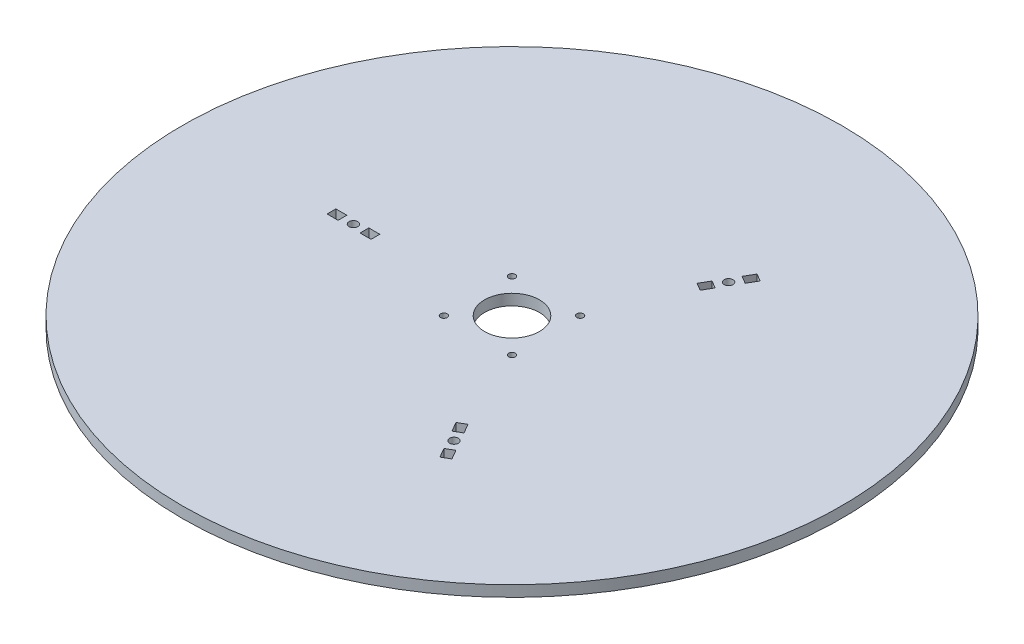
SolidWorks part; units mm, degrees
ref_plane "前视基准面" through (0, 0, 0) normal (0, 0, 1) x (1, 0, 0)
ref_plane "上视基准面" through (0, 0, 0) normal (0, 1, 0) x (1, 0, 0)
ref_plane "右视基准面" through (0, 0, 0) normal (1, 0, 0) x (0, 0, -1)
sketch "草图1" plane through (0, 0, 0) normal (0, 1, 0) x (1, 0, 0)
  line L0 (-72.1688, 0) -> (36.0844, -62.5) construction
  line L1 (15.5, -15.5) -> (-15.5, -15.5) construction
  line L2 (15.5, -15.5) -> (15.5, 15.5) construction
  line L3 (15.5, 15.5) -> (-15.5, 15.5) construction
  line L4 (-15.5, -15.5) -> (-15.5, 15.5) construction
  line L5 (15.5, -15.5) -> (-15.5, 15.5) construction
  line L6 (15.5, 15.5) -> (-15.5, -15.5) construction
  line L7 (-82.1688, 10) -> (-62.1688, 10) construction
  line L8 (-82.1688, -10) -> (-102.1688, -10) construction
  line L9 (-82.1688, -10) -> (-82.1688, 10) construction
  line L10 (-82.1688, 10) -> (-102.1688, 10) construction
  line L11 (-102.1688, -10) -> (-102.1688, 10) construction
  line L12 (-82.1688, -10) -> (-102.1688, 10) construction
  line L13 (-82.1688, 10) -> (-102.1688, -10) construction
  line L14 (-62.1688, 10) -> (-62.1688, -10) construction
  line L15 (-62.1688, -10) -> (-82.1688, -10) construction
  line L16 (-82.1688, 10) -> (-62.1688, -10) construction
  line L17 (36.8523, 67.8301) -> (40.3164, 65.8301)
  line L18 (-62.1688, -2) -> (-67.1688, -2)
  line L19 (-62.1688, -2) -> (-62.1688, 2)
  line L20 (-62.1688, 2) -> (-67.1688, 2)
  line L21 (-67.1688, -2) -> (-67.1688, 2)
  line L22 (-62.1688, -2) -> (-67.1688, 2) construction
  line L23 (-62.1688, 2) -> (-67.1688, -2) construction
  line L24 (-77.1688, -2) -> (-82.1688, -2)
  line L25 (-77.1688, -2) -> (-77.1688, 2)
  line L26 (-77.1688, 2) -> (-82.1688, 2)
  line L27 (-82.1688, -2) -> (-82.1688, 2)
  line L28 (-77.1688, -2) -> (-82.1688, 2) construction
  line L29 (-77.1688, 2) -> (-82.1688, -2) construction
  line L30 (36.8523, 67.8301) -> (39.3523, 72.1603)
  line L31 (39.3523, 72.1603) -> (42.8164, 70.1603)
  line L32 (40.3164, 65.8301) -> (42.8164, 70.1603)
  line L33 (29.3523, 54.8397) -> (32.8164, 52.8397)
  line L34 (29.3523, 54.8397) -> (31.8523, 59.1699)
  line L35 (31.8523, 59.1699) -> (35.3164, 57.1699)
  line L36 (32.8164, 52.8397) -> (35.3164, 57.1699)
  line L37 (40.3164, -65.8301) -> (36.8523, -67.8301)
  line L38 (40.3164, -65.8301) -> (42.8164, -70.1603)
  line L39 (42.8164, -70.1603) -> (39.3523, -72.1603)
  line L40 (36.8523, -67.8301) -> (39.3523, -72.1603)
  line L41 (32.8164, -52.8397) -> (29.3523, -54.8397)
  line L42 (32.8164, -52.8397) -> (35.3164, -57.1699)
  line L43 (35.3164, -57.1699) -> (31.8523, -59.1699)
  line L44 (29.3523, -54.8397) -> (31.8523, -59.1699)
  line L45 (49.7446, 66.1603) -> (59.7446, 83.4808) construction
  line L46 (42.4241, 93.4808) -> (59.7446, 83.4808) construction
  line L47 (32.4241, 76.1603) -> (42.4241, 93.4808) construction
  line L48 (32.4241, 76.1603) -> (49.7446, 66.1603) construction
  line L49 (32.4241, -76.1603) -> (42.4241, -93.4808) construction
  line L50 (59.7446, -83.4808) -> (42.4241, -93.4808) construction
  line L51 (49.7446, -66.1603) -> (59.7446, -83.4808) construction
  line L52 (49.7446, -66.1603) -> (32.4241, -76.1603) construction
  line L53 (29.7446, 31.5192) -> (39.7446, 48.8397) construction
  line L54 (-42.1688, -10) -> (-62.1688, -10) construction
  line L55 (-42.1688, -10) -> (-42.1688, 10) construction
  line L56 (-42.1688, 10) -> (-62.1688, 10) construction
  line L57 (-62.1688, -10) -> (-62.1688, 10) construction
  line L58 (-42.1688, -10) -> (-62.1688, 10) construction
  line L59 (-42.1688, 10) -> (-62.1688, -10) construction
  line L60 (12.4241, 41.5192) -> (29.7446, 31.5192) construction
  line L61 (12.4241, 41.5192) -> (22.4241, 58.8397) construction
  line L62 (39.7446, 48.8397) -> (22.4241, 58.8397) construction
  line L63 (12.4241, -41.5192) -> (22.4241, -58.8397) construction
  line L64 (29.7446, -31.5192) -> (12.4241, -41.5192) construction
  line L65 (29.7446, -31.5192) -> (39.7446, -48.8397) construction
  line L66 (22.4241, -58.8397) -> (39.7446, -48.8397) construction
  circle A0 centre (0, 0) radius 150
  circle A1 centre (-15.5, 15.5) radius 1.5
  circle A2 centre (15.5, 15.5) radius 1.5
  circle A3 centre (15.5, -15.5) radius 1.5
  circle A4 centre (-15.5, -15.5) radius 1.5
  circle A5 centre (0, 0) radius 12.5
  circle A6 centre (-72.1688, 0) radius 2
  circle A7 centre (36.0844, 62.5) radius 2
  circle A8 centre (36.0844, -62.5) radius 2
  circle A14 centre (0, 0) radius 72.1688 construction
  point P17 (0, 0)
  point P18 (-92.1688, 0)
  point P27 (-79.6688, 0)
  point P28 (-72.1688, 0)
  point P29 (-64.6688, 0)
  point P38 (-52.1688, 0)
  point P61 (0, 0)
  point P68 (0, 0)
  point P71 (0, 0)
  point P81 (0, 0)
  dimension "D1" = 300
  dimension "D4" = 3
  dimension "D6" = 25
  dimension "D7" = 125
  dimension "D10" = 4
  dimension "D18" = 166.9615
  dimension "D19" = 20
  dimension "D12" = 3
  dimension "D2" = 31
  dimension "D3" = 31
  dimension "D8" = 20
  dimension "D9" = 20
  dimension "D11" = 20
  dimension "D13" = 4
  dimension "D14" = 4
  dimension "D15" = 5
  dimension "D16" = 5
  dimension "D21" = 97.6795
  dimension "D5" = 4
  dimension "D17" = 3
  dimension "D20" = 3
extrude "凸台-拉伸1" add sketch "草图1" along normal blind 5
